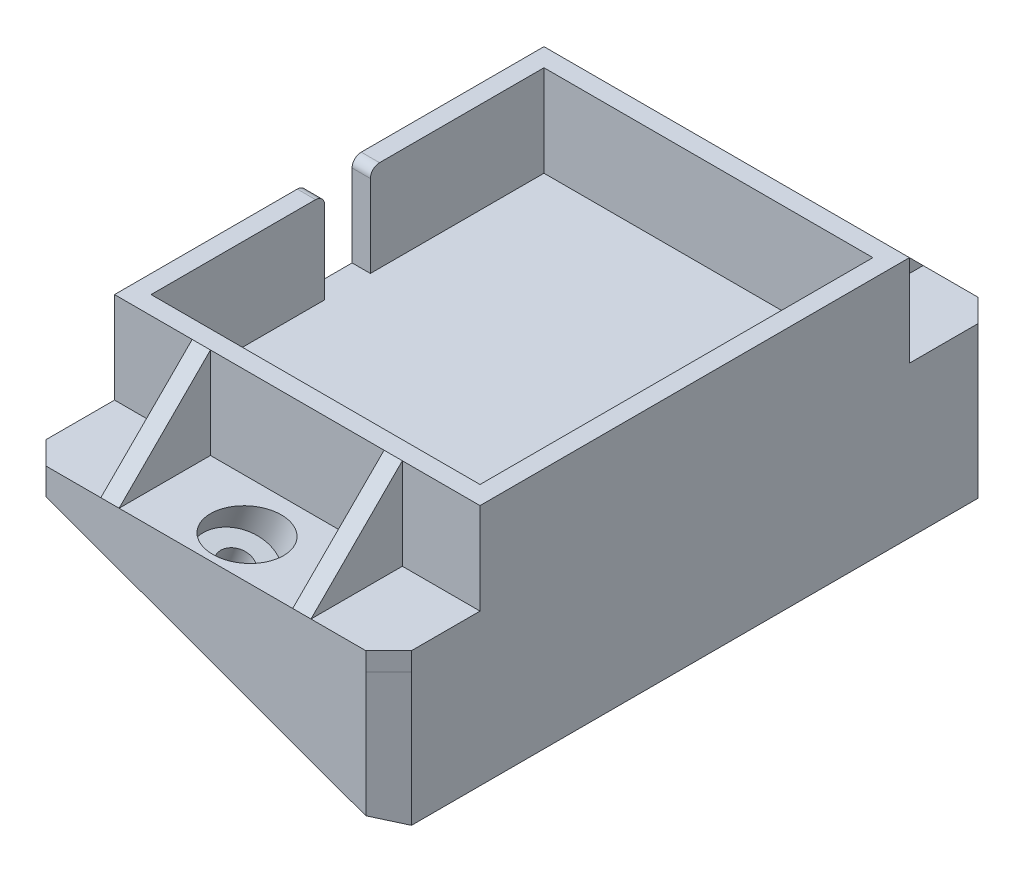
SolidWorks part; units mm, degrees
ref_plane "Front Plane" through (0, 0, 0) normal (0, 0, 1) x (1, 0, 0)
ref_plane "Top Plane" through (0, 0, 0) normal (0, 1, 0) x (1, 0, 0)
ref_plane "Right Plane" through (0, 0, 0) normal (1, 0, 0) x (0, 0, -1)
sketch "Sketch1" plane through (0, 0, 0) normal (0, 1, 0) x (1, 0, 0)
  line L5 (-40, 47) -> (40, 47)
  line L6 (-36, 43) -> (36, 43)
  line L10 (-36, 43) -> (-36, -43)
  line L11 (-36, -43) -> (36, -43)
  line L12 (36, 43) -> (36, -43)
  line L13 (-36, 43) -> (36, -43) construction
  line L14 (-36, -43) -> (36, 43) construction
  line L15 (40, 47) -> (40, -47)
  line L16 (-40, -47) -> (40, -47)
  line L17 (-40, 47) -> (-40, -47)
  point P0 (0, 0)
  dimension "D1" = 86
  dimension "D2" = 72
  dimension "D3" = 4
extrude "Boss-Extrude3" add sketch "Sketch1" along normal blind 20
sketch "Sketch10" plane through (0, 0, 0) normal (0, -1, 0) x (1, 0, 0)
  line L11 (-40, -47) -> (-40, 47) construction
  line L12 (0, 0) -> (-46.4736, 0) construction
  line L18 (-40, -67) -> (40, -67)
  line L19 (-40, -67) -> (-40, 67)
  line L20 (-40, 67) -> (40, 67)
  line L21 (40, -67) -> (40, 67)
  line L22 (-40, -67) -> (40, 67) construction
  line L23 (-40, 67) -> (40, -67) construction
  line L24 (-40, 47) -> (40, 47) construction
  point P0 (0, 0)
  point P11 (0, 57)
  point P16 (0, -57)
  dimension "D1" = 20
  dimension "D2" = 10
extrude "Boss-Extrude4" add sketch "Sketch10" along normal blind 4
sketch "Sketch11" plane through (-40, 0, 0) normal (-1, 0, 0) x (0, 0, 1)
  line L0 (0, 0) -> (0, 37.1567) construction
  line L1 (5, 20) -> (5, 0)
  line L2 (-47, 20) -> (47, 20) construction
  line L3 (5, 0) -> (-5, 0)
  line L4 (-5, 0) -> (-5, 20)
  line L5 (-5, 20) -> (5, 20)
  dimension "D1" = 5
  dimension "D2" = 10
extrude "Cut-Extrude1" cut sketch "Sketch11" against normal up to next
fillet "Fillet2" radius 2 2 edges at (-38, 20, -5) (-38, 20, 5)
sketch "Sketch24" plane through (0, 0, 0) normal (0, 1, 0) x (1, 0, 0)
  point P0 (0, 57)
  point P2 (0, -57)
ref_plane "Plane5" through (-21, 0, 0) normal (-1, 0, 0) x (0, 0, 1)
sketch "Sketch26" plane through (-21, 0, 0) normal (-1, 0, 0) x (0, 0, 1)
  line L0 (-67, 0) -> (-47, 20)
rib "Rib10" sketch "Sketch26" sketch "Sketch26" thickness 4 extrusion direction parallel to sketch draft on no parameters "D1"=4
mirror "Mirror3" about plane through (0, 0, 0) normal (1, 0, 0) of "Rib10"
mirror "Mirror4" about plane through (0, 0, 0) normal (0, 0, 1) of "Rib10", "Mirror3"
chamfer "Chamfer1" distance 5 angle 45 4 edges at (40, -2, 67) (-40, -2, 67) (40, -2, -67) (-40, -2, -67)
sketch "Sketch29" plane through (0, 0, 0) normal (0, 0, 1) x (1, 0, 0)
  line L0 (40, -4) -> (35, -4) construction
  line L1 (35, -4) -> (-35, -4) construction
  line L2 (-35, -4) -> (-40, -4) construction
  line L3 (40, -4) -> (35, -4)
  line L4 (35, -4) -> (-35, -4)
  line L5 (-35, -4) -> (-40, -4)
  line L6 (40, -4) -> (40, -33.1176)
  line L7 (40, -33.1176) -> (-40, -4)
  dimension "D1" = 20
extrude "Boss-Extrude6" add sketch "Sketch29" along normal up to surface and the other way up to surface up to face at (0, -1, 67) other way up to face at (0, -1, -67)
chamfer "Chamfer2" distance 5 angle 45 2 edges at (40, -18.5588, -67) (40, -18.5588, 67)
sketch "Sketch30" plane through (0, -4, 0) normal (0, 1, 0) x (1, 0, 0)
  line L0 (-40, -67) -> (-35, -67) construction
  line L1 (-35, -67) -> (-40, -62) construction
  line L2 (-40, -62) -> (-40, -67) construction
  line L3 (-40, 67) -> (-40, 62) construction
  line L4 (-40, 62) -> (-35, 67) construction
  line L5 (-35, 67) -> (-40, 67) construction
  line L6 (-40, -67) -> (-35, -67)
  line L7 (-35, -67) -> (-40, -62)
  line L8 (-40, -62) -> (-40, -67)
  line L9 (-40, 67) -> (-40, 62)
  line L10 (-40, 62) -> (-35, 67)
  line L11 (-35, 67) -> (-40, 67)
extrude "Cut-Extrude2" cut sketch "Sketch30" against normal blind 10
ref_plane "Plane6" through (4.2959, 11.8029, 0) normal (-0.342, -0.9397, 0) x (-0.9397, 0.342, 0)
sketch "Sketch32" plane through (4.2959, 11.8029, 0) normal (-0.342, -0.9397, 0) x (-0.9397, 0.342, 0)
  line L0 (0, 0) -> (0, 58) construction
  circle A0 centre (0, 58) radius 7.5
  dimension "D2" = 15
  dimension "D1" = 58
extrude "Cut-Extrude3" cut sketch "Sketch32" along normal blind 20
sketch "Sketch33" plane through (-2.5445, -6.9909, 0) normal (0.342, 0.9397, 0) x (0.9397, -0.342, 0)
  line L0 (-17.8542, 67) -> (17.8542, 67) construction
  circle A2 centre (0, 58) radius 3.4
  dimension "D1" = 6.8
  dimension "D2" = 9
extrude "Cut-Extrude5" cut sketch "Sketch33" against normal up to surface (10 mm away) up to face at (0, -18.5588, 0)
mirror "Mirror5" about plane through (0, 0, 0) normal (0, 0, 1) of "Cut-Extrude5", "Cut-Extrude3"
